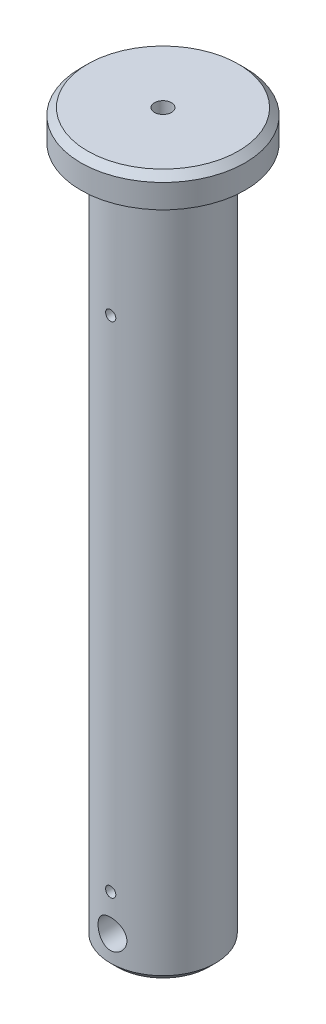
SolidWorks part; units mm, degrees
material "AISI 1045 Aço, trefilado"
ref_plane "Plano frontal" through (0, 0, 0) normal (0, 0, 1) x (1, 0, 0)
ref_plane "Plano superior" through (0, 0, 0) normal (0, 1, 0) x (1, 0, 0)
ref_plane "Plano direito" through (0, 0, 0) normal (1, 0, 0) x (0, 0, -1)
sketch "Esboço1" plane through (0, 0, 0) normal (1, 0, 0) x (0, 0, -1)
  line L0 (0, 121.75) -> (0, -121.75) construction
  line L1 (2.5, 91.1491) -> (22.25, 91.1491)
  line L2 (24.25, 89.1491) -> (24.25, 82.1491)
  line L3 (24.25, 82.1491) -> (15.5, 82.1491)
  line L4 (15.5, 82.1491) -> (15.5, -119.75)
  line L5 (13.5, -121.75) -> (0, -121.75)
  line L6 (22.25, 91.1491) -> (24.25, 89.1491)
  line L7 (15.5, -119.75) -> (13.5, -121.75)
  line L8 (2.5, 91.1491) -> (2.5, 81.75)
  line L9 (2.5, 81.75) -> (1.5, 81.1491)
  line L10 (1.5, 81.1491) -> (1.5, -80.8487)
  line L11 (1.5, -80.8487) -> (0, -81.75)
  line L12 (0, -121.75) -> (0, -81.75)
  point P4 (24.25, 91.1491)
  point P7 (15.5, -121.75)
  dimension "D1" = 243.5
  dimension "D2" = 31
  dimension "D3" = 48.5
  dimension "D4" = 9
  dimension "D5" = 59
  dimension "D6" = 3
  dimension "D9" = 5
  dimension "D10" = 59
  dimension "D11" = 10
  dimension "D12" = 40
revolve "Revolução1" add sketch "Esboço1" angle 360 about L0
cosmetic thread "Representação de rosca1" parameters "D2"=6
sketch "Esboço2" plane through (0, 0, 0) normal (0, 0, 1) x (1, 0, 0)
  line L0 (0, 91.1491) -> (0, 45.7991) construction
  line L1 (22.25, 91.1491) -> (-22.25, 91.1491) construction
  line L2 (0, 45.7991) -> (0, -101.5009) construction
  circle A0 centre (0, 45.7991) radius 1.5
  circle A1 centre (0, -101.5009) radius 1.5
  dimension "D2" = 3
  dimension "D1" = 45.35
  dimension "D3" = 192.65
extrude "Corte-extrusão1" cut sketch "Esboço2" along normal through all
sketch "Esboço3" plane through (0, 0, 0) normal (0, 0, 1) x (1, 0, 0)
  line L0 (0, -121.75) -> (0, -112.25) construction
  line L1 (-13.5, -121.75) -> (13.5, -121.75) construction
  circle A0 centre (0, -112.25) radius 4.25
  dimension "D1" = 8.5
  dimension "D2" = 9.5
extrude "Corte-extrusão2" cut sketch "Esboço3" against normal through all both and the other way through all
